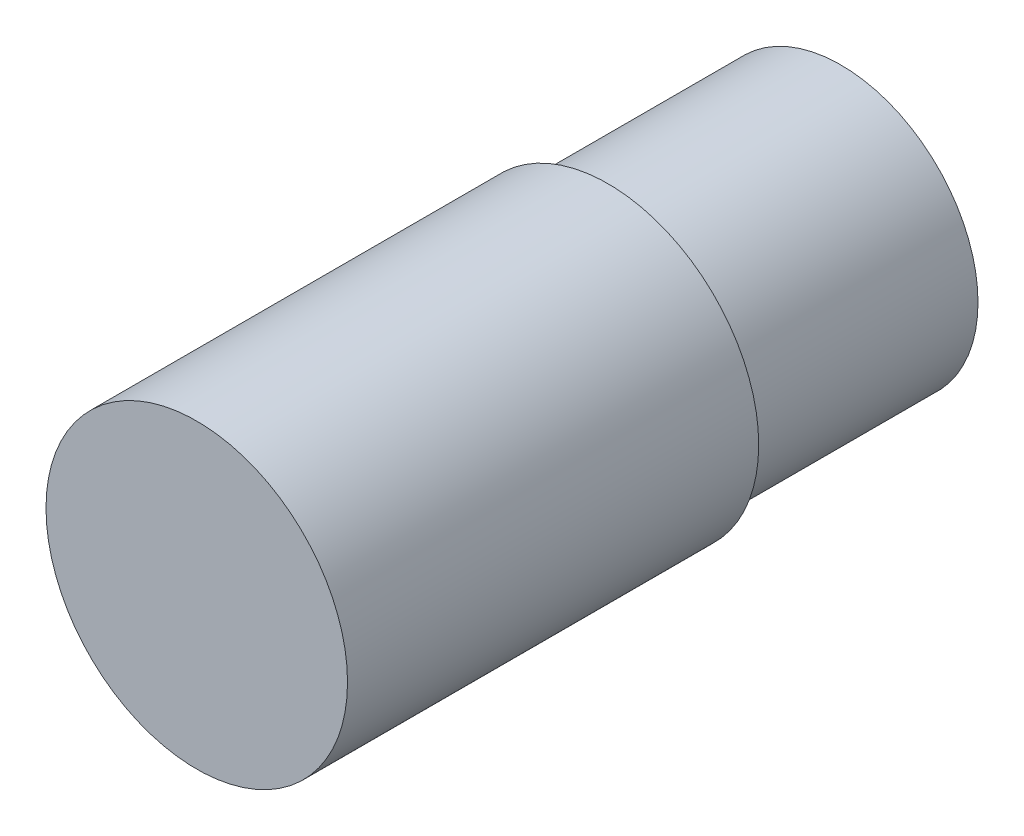
SolidWorks part; units mm, degrees
ref_plane "Front Plane" through (0, 0, 0) normal (0, 0, 1) x (1, 0, 0)
ref_plane "Top Plane" through (0, 0, 0) normal (0, 1, 0) x (1, 0, 0)
ref_plane "Right Plane" through (0, 0, 0) normal (1, 0, 0) x (0, 0, -1)
sketch "Sketch1" plane through (0, 0, 0) normal (0, 0, 1) x (1, 0, 0)
  circle A0 centre (0, 0) radius 10
  dimension "D1" = 20
extrude "Boss-Extrude1" add sketch "Sketch1" along normal blind 17
sketch "Sketch2" plane through (0, 0, 17) normal (0, 0, 1) x (1, 0, 0)
  circle A0 centre (0, 0) radius 11
  dimension "D1" = 22
extrude "Boss-Extrude2" add sketch "Sketch2" along normal blind 30
